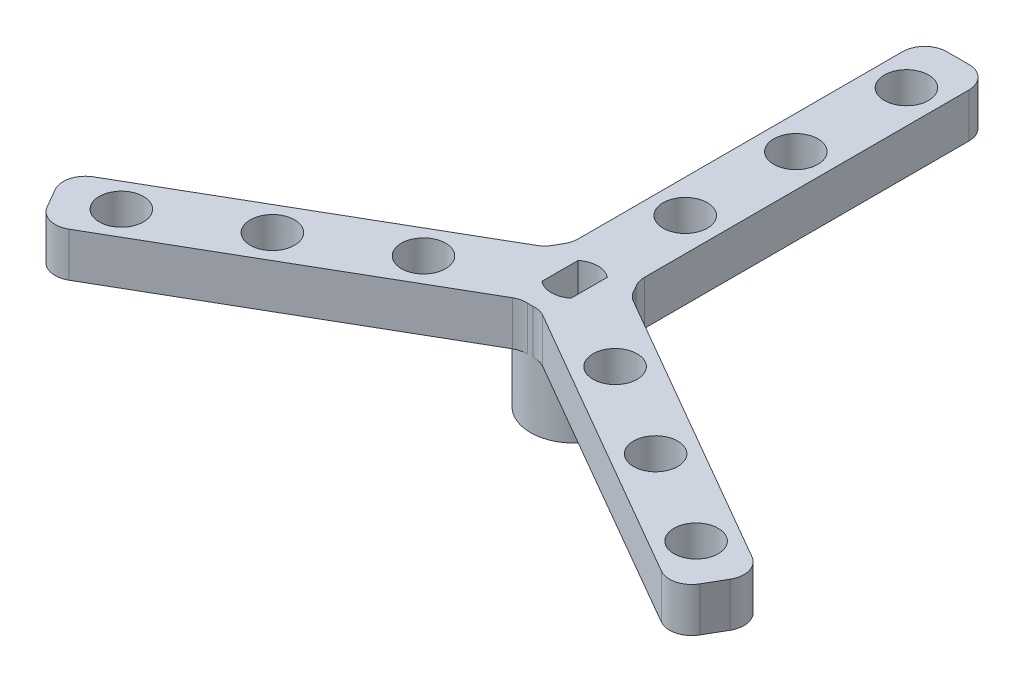
SolidWorks part; units mm, degrees
ref_plane "Front Plane" through (0, 0, 0) normal (0, 0, 1) x (1, 0, 0)
ref_plane "Top Plane" through (0, 0, 0) normal (0, 1, 0) x (1, 0, 0)
ref_plane "Right Plane" through (0, 0, 0) normal (1, 0, 0) x (0, 0, -1)
sketch "Sketch1" plane through (0, 0, 0) normal (0, 1, 0) x (1, 0, 0)
  line L0 (1.6875, 5.7641) -> (1.6875, 1.6674)
  line L2 (-1.3625, 5.6407) -> (-1.3625, 1.7907)
  line L4 (1.4375, 5.6407) -> (1.4375, 1.7907)
  line L5 (-1.6125, 5.7641) -> (-1.6125, 1.6674)
  arc A1 (-1.3625, 5.6407) -> (1.4375, 5.6407) centre (0.0375, 3.7161) cw
  arc A2 (-1.3625, 1.7907) -> (1.4375, 1.7907) centre (0.0375, 3.7154) ccw
  arc A3 (-1.6125, 5.7641) -> (1.6875, 5.7641) centre (0.0375, 3.7161) cw
  arc A4 (-1.6125, 1.6674) -> (1.6875, 1.6674) centre (0.0375, 3.7154) ccw
  circle A5 centre (0.0375, 3.7154) radius 5
  dimension "D1" = 3.85
  dimension "D3" = 2.38
  dimension "D4" = 2.38
  dimension "D6" = 10
  dimension "D2" = 2.8
  dimension "D5" = 0.25
extrude "Boss-Extrude1" add sketch "Sketch1" along normal blind 12.5 contours A5 A4 L5 A3 L0
sketch "Sketch2" plane through (0, 12.5, 0) normal (0, 1, 0) x (1, 0, 0)
  line L0 (0.0375, 47.0226) -> (0.0375, 7.0226) construction
  line L1 (0.0375, 8.7154) -> (0.0375, 9.9323) construction
  line L2 (4.7766, 5.3094) -> (1.0266, -1.1858)
  line L3 (-3.7125, 7.0226) -> (3.7875, 7.0226)
  line L4 (-3.7125, 7.0226) -> (-3.7125, 47.0226)
  line L5 (3.7875, 7.0226) -> (3.7875, 47.0226)
  line L6 (-3.7125, 47.0226) -> (3.7875, 47.0226)
  line L7 (4.7766, 5.3094) -> (39.4176, -14.6906)
  line L8 (1.0266, -1.1858) -> (35.6676, -21.1858)
  line L9 (39.4176, -14.6906) -> (35.6676, -21.1858)
  line L10 (37.5426, -17.9382) -> (2.9016, 2.0618) construction
  line L11 (-4.7016, 5.3094) -> (-0.9516, -1.1858)
  line L12 (-4.7016, 5.3094) -> (-39.3427, -14.6906)
  line L13 (-0.9516, -1.1858) -> (-35.5927, -21.1858)
  line L14 (-39.3427, -14.6906) -> (-35.5927, -21.1858)
  line L15 (-2.8266, 2.0618) -> (-37.4677, -17.9382) construction
  circle A0 centre (0.0375, 3.7154) radius 5 construction
  point P6 (0.0375, 3.7154)
  point P24 (0, 0)
  point P25 (0, 0)
  dimension "D1" = 7.5
  dimension "D2" = 40
  dimension "D3" = 0
  dimension "D4" = 7.5
  dimension "D5" = 40
  dimension "D6" = 120
  dimension "D7" = 7.5
  dimension "D8" = 40
  dimension "D9" = 120
extrude "Boss-Extrude4" add sketch "Sketch2" against normal blind 5
sketch "Sketch4" plane through (0, 12.5, 0) normal (0, 1, 0) x (1, 0, 0)
  line L0 (3.7875, 7.0226) -> (3.7875, 47.0226) construction
  line L1 (0.0375, 3.7161) -> (37.5426, -17.9382) construction
  line L2 (35.6676, -21.1858) -> (39.4176, -14.6906) construction
  line L3 (0.0375, 3.7161) -> (-37.4677, -17.9382) construction
  line L4 (-39.3427, -14.6906) -> (-35.5927, -21.1858) construction
  circle A0 centre (0.0375, 16.2161) radius 2.5
  circle A1 centre (0.0375, 28.7161) radius 2.5
  circle A2 centre (0.0375, 41.2161) radius 2.5
  circle A3 centre (-10.788, -2.5337) radius 2.5
  circle A4 centre (-21.6135, -8.7834) radius 2.5
  circle A5 centre (-32.439, -15.0331) radius 2.5
  circle A6 centre (10.8629, -2.5337) radius 2.5
  circle A7 centre (21.6884, -8.7834) radius 2.5
  circle A8 centre (32.5139, -15.0331) radius 2.5
  point P5 (0.0375, 3.7161)
  dimension "D1" = 5
  dimension "D2" = 5
  dimension "D7" = 5
  dimension "D3" = 12.5
  dimension "D4" = 12.5
  dimension "D5" = 3.75
  dimension "D6" = 3.75
  dimension "D8" = 3.75
  dimension "D9" = 12.5
extrude "Cut-Extrude1" cut sketch "Sketch4" against normal blind 100
fillet "Fillet1" radius 2.5 6 edges at (4.7766, 10, -5.3094) (3.7875, 10, -7.0226) (-3.7125, 10, -7.0226) (-4.7016, 10, -5.3094) (-0.9516, 10, 1.1858) (1.0266, 10, 1.1858)
fillet "Fillet2" radius 2.5 6 edges at (-3.7125, 10, -47.0226) (3.7875, 10, -47.0226) (39.4176, 10, 14.6906) (35.6676, 10, 21.1858) (-39.3427, 10, 14.6906) (-35.5927, 10, 21.1858)
